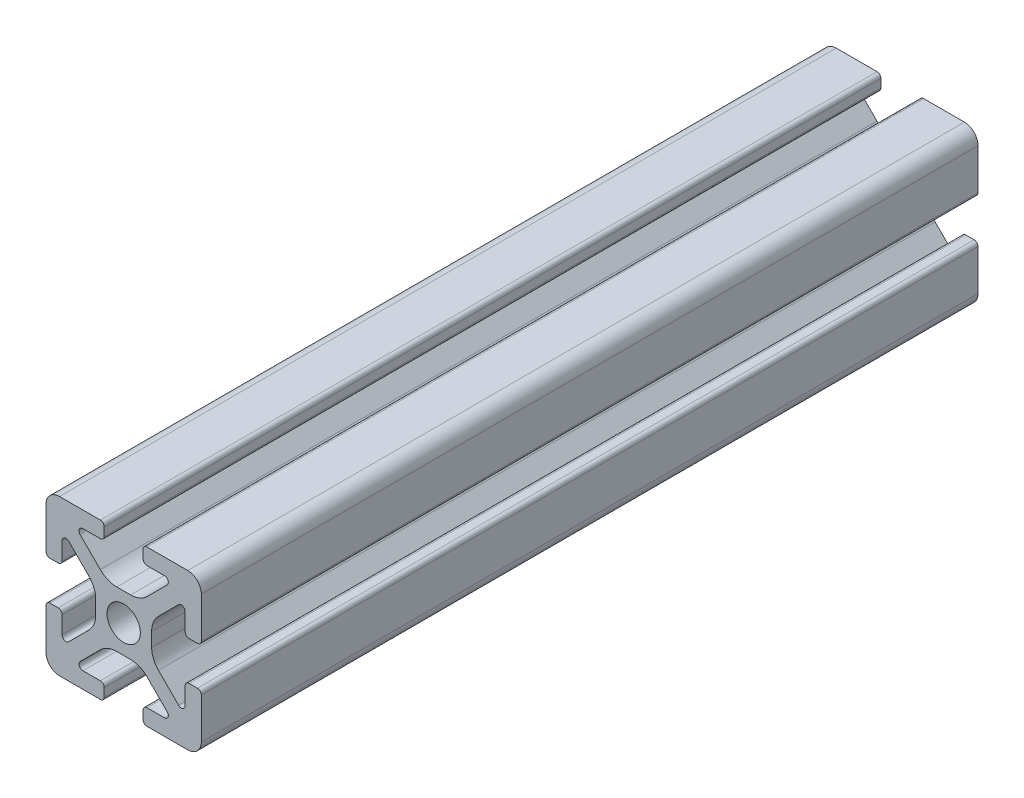
SolidWorks part; units mm, degrees
material "1060 Alloy"
ref_plane "Front Plane" through (0, 0, 0) normal (0, 0, 1) x (1, 0, 0)
ref_plane "Top Plane" through (0, 0, 0) normal (0, 1, 0) x (1, 0, 0)
ref_plane "Right Plane" through (0, 0, 0) normal (1, 0, 0) x (0, 0, -1)
sketch "Sketch2" plane through (0, 0, 0) normal (0, 0, 1) x (1, 0, 0)
  line L0 (0, 10) -> (0, -10) construction
  line L1 (-10, 0) -> (10, 0) construction
  line L2 (2.5, -10) -> (10, -10)
  line L3 (10, -10) -> (10, -2.5)
  line L4 (2.5, -10) -> (2.5, -7.9246)
  line L5 (2.5, -7.9246) -> (6.4571, -7.9246)
  line L6 (6.4571, -7.9246) -> (2.1325, -3.6)
  line L7 (0, 0) -> (10, -10) construction
  line L8 (10, -2.5) -> (7.9246, -2.5)
  line L9 (7.9246, -2.5) -> (7.9246, -6.4571)
  line L10 (7.9246, -6.4571) -> (3.6, -2.1325)
  line L11 (5.7623, -4.2948) -> (4.2948, -5.7623) construction
  circle A0 centre (0, 0) radius 2.15
  arc A1 (5.25, -7.9246) -> (5.6036, -7.0711) centre (5.25, -7.4246) ccw construction
  point P8 (0, -3.6)
  point P16 (5.0286, -5.0286)
  dimension "Center Hole Diameter" = 4.3
  dimension "D3" = 0.5
  dimension "Rail Height" = 20
  dimension "Rail Width" = 20
  dimension "T-Slot Width" = 5
  dimension "Slot Depth" = 6.4
  dimension "Slot Inner Width" = 11.5
sketch "Sketch3" plane through (0, 0, 0) normal (1, 0, 0) x (0, 0, -1)
  line L0 (-76.2, -10) -> (76.2, -10) construction
  line L1 (-50.8, 0) -> (50.8, 0) construction
  line L2 (0, 10) -> (0, -10) construction
  line L3 (0, 10) -> (0, -10) construction
  point P6 (-50.8, 0)
  point P8 (50.8, 0)
  dimension "Length" = 152.4
  dimension "D1" = 25.4
sketch "Sketch4" plane through (0, 0, 0) normal (0, 0, 1) x (1, 0, 0)
  line L0 (3, -10) -> (8.25, -10)
  line L1 (2.5, -10) -> (10, -10) construction
  line L2 (2.5, -10) -> (2.5, -7.9246) construction
  line L3 (2.5, -7.9246) -> (6.4571, -7.9246) construction
  line L4 (2.5, -8.4246) -> (2.5, -9.5)
  line L5 (3, -7.9246) -> (5.25, -7.9246)
  line L6 (0, -3.6) -> (0.8898, -3.6)
  line L7 (6.4571, -7.9246) -> (2.1325, -3.6) construction
  line L8 (3.0112, -4.4787) -> (5.6036, -7.0711)
  line L9 (10, -10) -> (10, -2.5) construction
  line L10 (7.9246, -6.4571) -> (3.6, -2.1325) construction
  line L11 (7.9246, -2.5) -> (7.9246, -6.4571) construction
  line L12 (7.9246, -5.25) -> (7.9246, -3)
  line L13 (10, -2.5) -> (7.9246, -2.5) construction
  line L14 (8.4246, -2.5) -> (9.5, -2.5)
  line L15 (10, -3) -> (10, -8.25)
  line L16 (7.0711, -5.6036) -> (4.4787, -3.0112)
  line L17 (3.6, 0) -> (3.6, -0.8898)
  line L18 (-10, 0) -> (10, 0) construction
  line L19 (0, -3.6) -> (0, -2.15)
  line L20 (0, 10) -> (0, -10) construction
  line L21 (3.6, 0) -> (2.15, 0)
  arc A0 (2.5, -9.5) -> (3, -10) centre (3, -9.5) ccw
  arc A1 (5.25, -7.9246) -> (5.6036, -7.0711) centre (5.25, -7.4246) ccw construction
  arc A2 (2.5, -8.4246) -> (3, -7.9246) centre (3, -8.4246) cw
  arc A3 (5.25, -7.9246) -> (5.6036, -7.0711) centre (5.25, -7.4246) ccw
  arc A4 (0.8898, -3.6) -> (3.0112, -4.4787) centre (0.8898, -6.6) cw
  arc A5 (8.25, -10) -> (10, -8.25) centre (8.25, -8.25) ccw
  arc A6 (7.0711, -5.6036) -> (7.9246, -5.25) centre (7.4246, -5.25) ccw
  arc A7 (7.9246, -3) -> (8.4246, -2.5) centre (8.4246, -3) cw
  arc A8 (9.5, -2.5) -> (10, -3) centre (9.5, -3) cw
  arc A9 (4.4787, -3.0112) -> (3.6, -0.8898) centre (6.6, -0.8898) cw
  circle A10 centre (0, 0) radius 2.15 construction
  arc A11 (0, -2.15) -> (2.15, 0) centre (0, 0) ccw
  dimension "D1" = 1.75
  dimension "D2" = 3
extrude "Boss-Extrude1" add sketch "Sketch4" along normal mid plane 152.4
mirror "Mirror1" about plane through (0, 0, 0) normal (1, 0, 0) of bodies 134
mirror "Mirror2" about plane through (0, 0, 0) normal (0, 1, 0) of bodies 135
sketch "Sketch5" plane through (0, 0, 76.2) normal (0, 0, 1) x (1, 0, 0)
  line L1 (-13.9539, 12.3566) -> (13.8334, 12.3566)
  line L2 (-13.9539, 12.3566) -> (-13.9539, -13.6827)
  line L3 (-13.9539, -13.6827) -> (13.8334, -13.6827)
  line L4 (13.8334, 12.3566) -> (13.8334, -13.6827)
extrude "Cut-Extrude1" cut sketch "Sketch5" against normal blind 52.4
equation "\"D3@Sketch2\"=\"T-Slot Width@Sketch2\"*0.1"
equation "\"D1@Sketch4\"=\"D3@Sketch2\"*3.5"
equation "\"D2@Sketch4\"=\"D3@Sketch2\"*6"
equation "\"D1@Boss-Extrude1\"=\"Length@Sketch3\""
